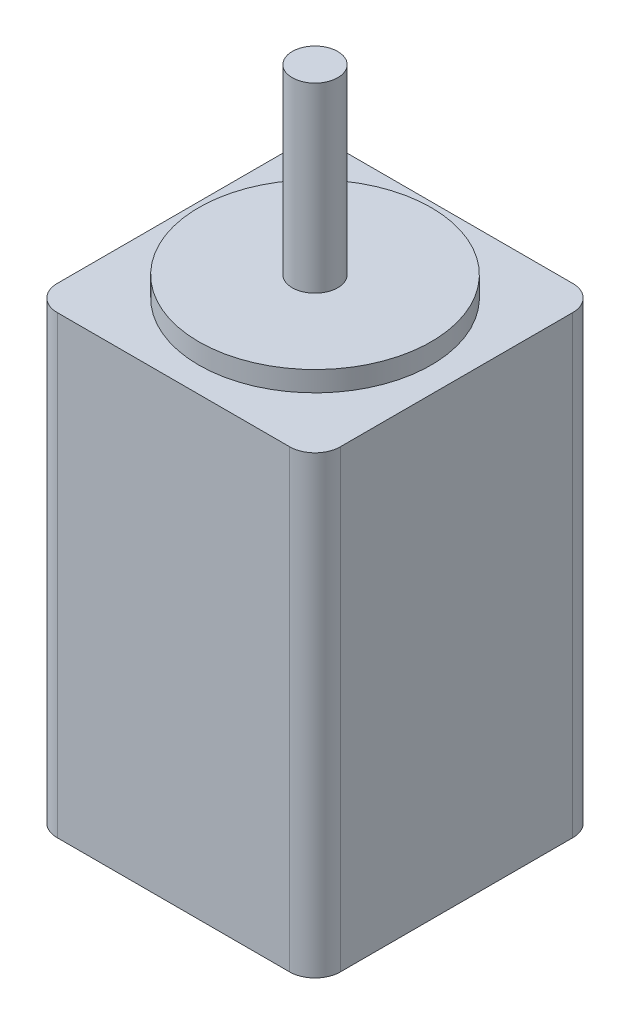
SolidWorks part; units mm, degrees
ref_plane "Front Plane" through (0, 0, 0) normal (0, 0, 1) x (1, 0, 0)
ref_plane "Top Plane" through (0, 0, 0) normal (0, 1, 0) x (1, 0, 0)
ref_plane "Right Plane" through (0, 0, 0) normal (1, 0, 0) x (0, 0, -1)
sketch "Sketch1" plane through (0, 0, 0) normal (0, 1, 0) x (1, 0, 0)
  line L0 (-14, -14) -> (14, -14)
  line L1 (-14, -14) -> (-14, 14)
  line L2 (14, -14) -> (14, 14)
  line L3 (-14, 14) -> (14, 14)
  line L4 (-14, -14) -> (14, 14) construction
  line L5 (14, -14) -> (-14, 14) construction
  point P1 (0, 0)
  dimension "D1" = 28
  dimension "D2" = 28
extrude "Boss-Extrude1" add sketch "Sketch1" along normal blind 45
sketch "Sketch2" plane through (0, 45, 0) normal (0, 1, 0) x (1, 0, 0)
  circle A0 centre (0, 0) radius 11.5
extrude "Boss-Extrude2" add sketch "Sketch2" along normal blind 2
sketch "Sketch3" plane through (0, 45, 0) normal (0, 1, 0) x (1, 0, 0)
  circle A0 centre (0, 0) radius 2.25
extrude "Boss-Extrude3" add sketch "Sketch3" along normal blind 20
fillet "Fillet1" radius 2.5 4 edges at (-14, 22.5, 14) (14, 22.5, 14) (14, 22.5, -14) (-14, 22.5, -14)
